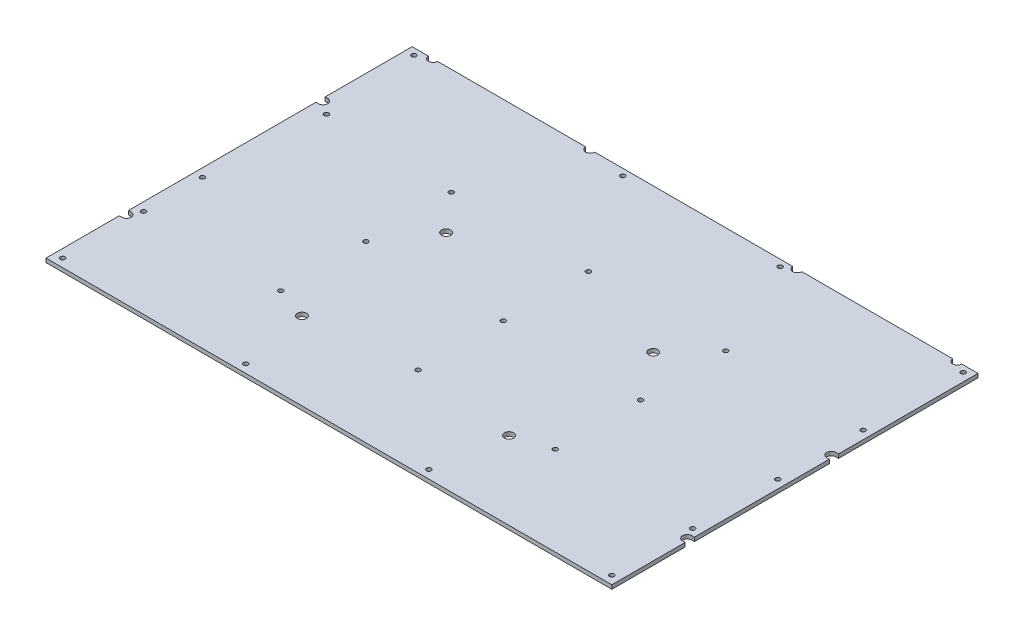
SolidWorks part; units mm, degrees
ref_plane "Front Plane" through (0, 0, 0) normal (0, 0, 1) x (1, 0, 0)
ref_plane "Top Plane" through (0, 0, 0) normal (0, 1, 0) x (1, 0, 0)
ref_plane "Right Plane" through (0, 0, 0) normal (1, 0, 0) x (0, 0, -1)
sketch "Sketch1" plane through (0, 0, 0) normal (0, 1, 0) x (1, 0, 0)
  line L1 (-215.9, -147.35) -> (215.9, -147.35)
  line L2 (-215.9, -147.35) -> (-215.9, 147.35)
  line L3 (-215.9, 147.35) -> (215.9, 147.35)
  line L4 (215.9, -147.35) -> (215.9, 147.35)
  line L5 (-215.9, -147.35) -> (215.9, 147.35) construction
  line L6 (-215.9, 147.35) -> (215.9, -147.35) construction
  point P0 (0, 0)
  dimension "D1" = 294.7
  dimension "D2" = 431.8
extrude "Boss-Extrude1" add sketch "Sketch1" along normal blind 3
sketch "Sketch2" plane through (0, 3, 0) normal (0, 1, 0) x (1, 0, 0)
  line L0 (-215.9, 147.35) -> (-215.9, -147.35) construction
  line L1 (-215.9, -147.35) -> (215.9, -147.35) construction
  line L2 (215.9, 147.35) -> (-215.9, 147.35) construction
  circle A0 centre (-209.55, -125.7) radius 1.775
  circle A1 centre (-209.55, 142.35) radius 1.775
  dimension "D3" = 3.55
  dimension "D5" = 6.35
  dimension "D6" = 3.55
  dimension "D1" = 6.35
  dimension "D2" = 21.65
  dimension "D4" = 5
extrude "Cut-Extrude1" cut sketch "Sketch2" against normal through all
pattern_linear "LPattern1" count 4 spacing 139.7 along (1, 0, 0) of "Cut-Extrude1"
sketch "Sketch3" plane through (0, 3, 0) normal (0, 1, 0) x (1, 0, 0)
  line L0 (-209.55, -64) -> (-209.55, -125.7) construction
  line L1 (215.9, 147.35) -> (-215.9, 147.35) construction
  circle A0 centre (-209.55, -64) radius 1.775
  dimension "D2" = 3.55
  dimension "D1" = 211.35
extrude "Cut-Extrude2" cut sketch "Sketch3" against normal through all
pattern_linear "LPattern2" count 5 spacing 104.77 along (1, 0, 0) count 3 spacing 65 along (0, 0, -1) skipping (0, 1), (0, 2) of "Cut-Extrude2"
sketch "Sketch4" plane through (0, 3, 0) normal (0, 1, 0) x (1, 0, 0)
  line L0 (-209.55, -19) -> (-209.55, -64) construction
  line L1 (-215.9, 147.35) -> (-215.9, -147.35) construction
  circle A0 centre (-203.9, 70) radius 1.775
  circle A2 centre (-104.78, 66) radius 1.775 construction
  circle A3 centre (-209.55, -64) radius 1.775 construction
  circle A4 centre (-209.55, -19) radius 1.775
  dimension "D1" = 4
  dimension "D2" = 45
  dimension "D3" = 12
extrude "Cut-Extrude3" cut sketch "Sketch4" against normal blind 10
sketch "Sketch7" plane through (0, 0, 0) normal (0, -1, 0) x (1, 0, 0)
  circle A0 centre (-213.9, -77.46) radius 3.5
  circle A1 centre (-213.9, 72.58) radius 3.5
  circle A2 centre (-200, 140.04) radius 3.5 construction
  circle A3 centre (-80, 140.04) radius 3.5 construction
  circle A4 centre (78, 140.04) radius 3.5 construction
  circle A5 centre (200, 140.04) radius 3.5 construction
  circle A6 centre (213.9, 72.58) radius 3.5
  circle A7 centre (213.9, -37.42) radius 3.5
  circle A8 centre (200, -147.42) radius 3.5
  circle A9 centre (78, -147.42) radius 3.5
  circle A10 centre (-80, -147.42) radius 3.5
  circle A11 centre (-80, -37.42) radius 3.5
  circle A12 centre (78, -37.42) radius 3.5
  circle A13 centre (78, 72.58) radius 3.5
  circle A14 centre (-80, 72.58) radius 3.5
  circle A15 centre (-200, -147.42) radius 3.5
  dimension "D1" = 7
extrude "Cut-Extrude5" cut sketch "Sketch7" against normal through all
sketch "Sketch8" plane through (0, 3, 0) normal (0, 1, 0) x (1, 0, 0)
  line L0 (215.9, 40.2923) -> (215.9, 147.35) construction
  line L1 (213.9, 33.92) -> (215.9, 33.92)
  line L2 (213.9, 33.92) -> (213.9, 40.92)
  line L3 (213.9, 40.92) -> (215.9, 40.92)
  line L4 (215.9, 33.92) -> (215.9, 40.92)
  line L5 (215.9, -69.7077) -> (215.9, 34.5477) construction
  line L6 (213.9, -69.08) -> (215.9, -69.08)
  line L7 (213.9, -69.08) -> (213.9, -76.08)
  line L8 (213.9, -76.08) -> (215.9, -76.08)
  line L9 (215.9, -69.08) -> (215.9, -76.08)
  line L10 (-215.9, 74.5877) -> (-215.9, -69.7077) construction
  line L11 (-213.9, 80.96) -> (-215.9, 80.96)
  line L12 (-213.9, 80.96) -> (-213.9, 73.96)
  line L13 (-213.9, 73.96) -> (-215.9, 73.96)
  line L14 (-215.9, 80.96) -> (-215.9, 73.96)
  line L15 (-215.9, -75.4523) -> (-215.9, -147.35) construction
  line L16 (-213.9, -69.08) -> (-215.9, -69.08)
  line L17 (-213.9, -69.08) -> (-213.9, -76.08)
  line L18 (-213.9, -76.08) -> (-215.9, -76.08)
  line L19 (-215.9, -69.08) -> (-215.9, -76.08)
  arc A0 (215.9, 40.2923) -> (215.9, 34.5477) centre (213.9, 37.42) ccw construction
  arc A1 (215.9, -69.7077) -> (215.9, -75.4523) centre (213.9, -72.58) ccw construction
  arc A2 (-215.9, 74.5877) -> (-215.9, 80.3323) centre (-213.9, 77.46) ccw construction
  arc A3 (-215.9, -75.4523) -> (-215.9, -69.7077) centre (-213.9, -72.58) ccw construction
extrude "Cut-Extrude6" cut sketch "Sketch8" against normal through all
sketch "Sketch9" plane through (0, 0, 0) normal (0, -1, 0) x (1, 0, 0)
  line L0 (-215.9, 76.08) -> (-215.9, 147.35) construction
  line L1 (215.9, 147.35) -> (-215.9, 147.35)
  line L2 (215.9, 147.35) -> (215.9, 132.05)
  line L3 (215.9, 132.05) -> (-215.9, 132.05)
  line L4 (-215.9, 147.35) -> (-215.9, 132.05)
  dimension "D1" = 15.3
extrude "Cut-Extrude7" cut sketch "Sketch9" against normal through all
sketch "Sketch11" plane through (0, 3, 0) normal (0, 1, 0) x (1, 0, 0)
  circle A0 centre (-69.85, 142.35) radius 1.775 construction
  circle A1 centre (-69.85, 142.35) radius 1.775
extrude "Boss-Extrude3" add sketch "Sketch11" against normal up to surface (3 mm away) up to face at (-0.1429, 0, -38.3771)
sketch "Sketch12" plane through (0, 3, 0) normal (0, 1, 0) x (1, 0, 0)
  line L0 (-50.15, 142.35) -> (69.85, 142.35) construction
  circle A0 centre (-50.15, 142.35) radius 1.775
  circle A1 centre (69.85, 142.35) radius 1.775 construction
  dimension "D1" = 120
extrude "Cut-Extrude8" cut sketch "Sketch12" against normal through all
sketch "Sketch13" plane through (0, 3, 0) normal (0, 1, 0) x (1, 0, 0)
  circle A0 centre (-154.35, 52.5675) radius 1.3533
